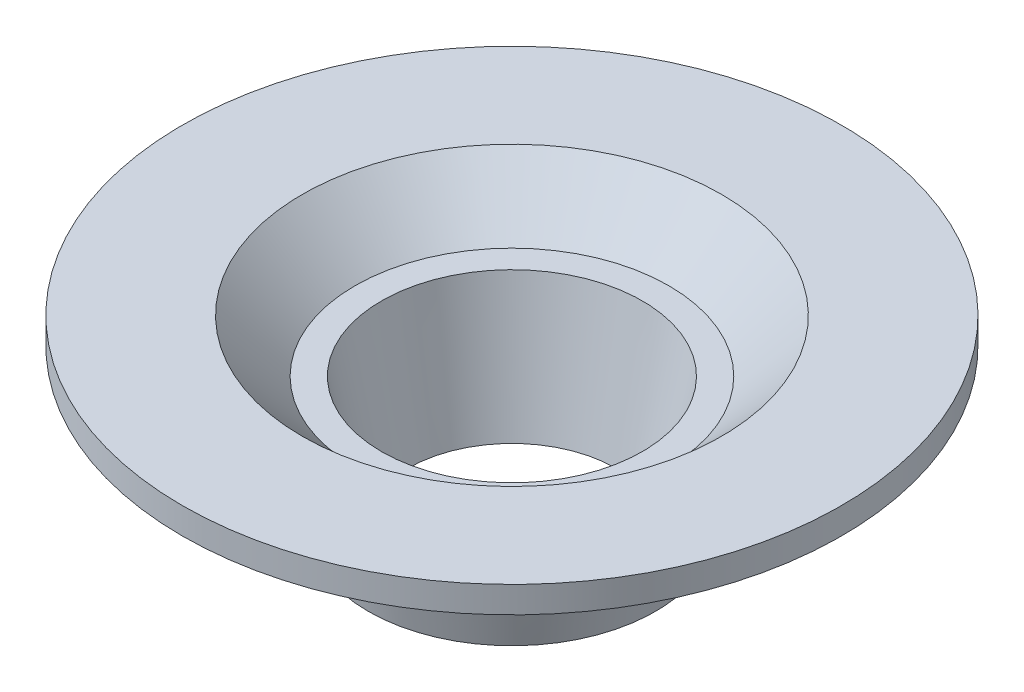
SolidWorks part; units mm, degrees
ref_plane "Front Plane" through (0, 0, 0) normal (0, 0, 1) x (1, 0, 0)
ref_plane "Top Plane" through (0, 0, 0) normal (0, 1, 0) x (1, 0, 0)
ref_plane "Right Plane" through (0, 0, 0) normal (1, 0, 0) x (0, 0, -1)
sketch "Sketch1" plane through (0, 0, 0) normal (0, 0, 1) x (1, 0, 0)
  line L0 (0, 0) -> (0, -5) construction
  line L1 (4.95, 0) -> (5.95, 0)
  line L2 (5.95, 0) -> (7.95, 2)
  line L3 (7.95, 2) -> (12.5, 2)
  line L4 (12.5, 2) -> (12.5, 1)
  line L5 (12.5, 1) -> (10.5, 1)
  line L6 (10.5, 1) -> (8.5, -1)
  line L7 (8.5, -1) -> (6.25, -1)
  line L8 (6.25, -1) -> (5.45, -5)
  line L9 (5.45, -5) -> (3.95, -5)
  line L10 (3.95, -5) -> (4.95, 0)
  point P5 (3.523, -5)
  point P14 (3.7219, -2.2566)
  point P15 (4.5186, 1.8852)
  point P16 (0, 0)
  point P17 (6.9992, -1)
  dimension "D1" = 5
  dimension "D2" = 7.9
  dimension "D3" = 2
  dimension "D4" = 2
  dimension "D5" = 1
  dimension "D6" = 2
  dimension "D7" = 4
  dimension "D8" = 12.5
  dimension "D9" = 1
  dimension "D10" = 1.5
  dimension "D11" = 9.9
  dimension "D12" = 25
revolve "Revolve1" add sketch "Sketch1" angle 360 about L0
